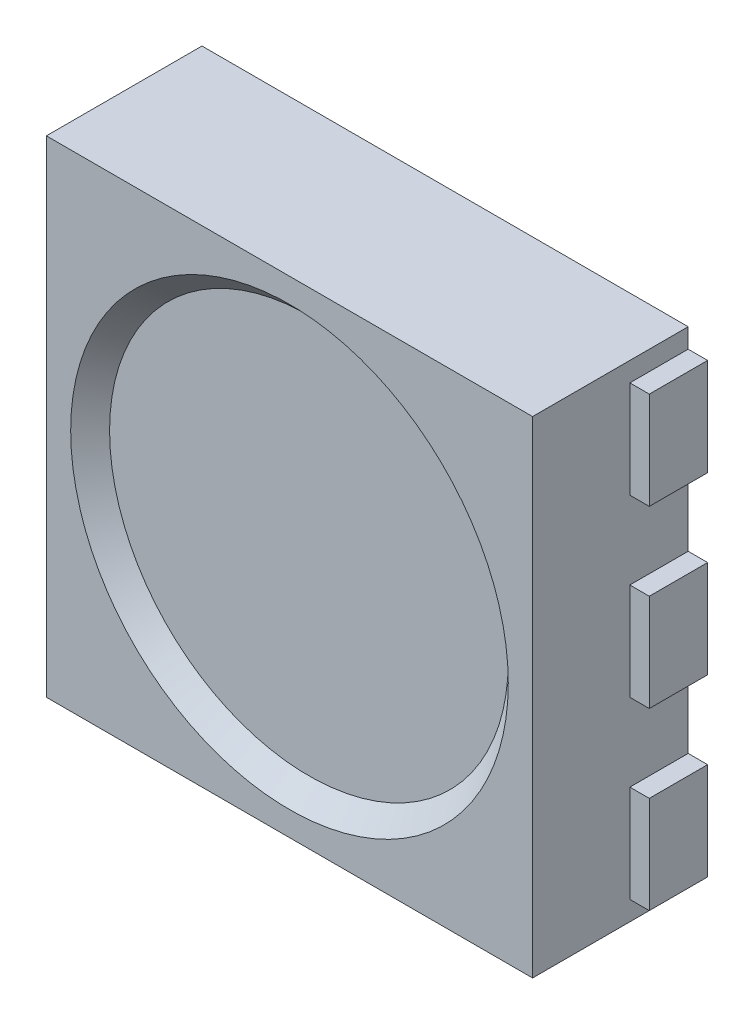
SolidWorks part; units mm, degrees
ref_plane "Front Plane" through (0, 0, 0) normal (0, 0, 1) x (1, 0, 0)
ref_plane "Top Plane" through (0, 0, 0) normal (0, 1, 0) x (1, 0, 0)
ref_plane "Right Plane" through (0, 0, 0) normal (1, 0, 0) x (0, 0, -1)
sketch "Sketch1" plane through (0, 0, 0) normal (0, 0, 1) x (1, 0, 0)
  line L1 (-2.5, 2.5) -> (2.5, 2.5)
  line L2 (-2.5, 2.5) -> (-2.5, -2.5)
  line L3 (-2.5, -2.5) -> (2.5, -2.5)
  line L4 (2.5, 2.5) -> (2.5, -2.5)
  line L5 (-2.5, 2.5) -> (2.5, -2.5) construction
  line L6 (-2.5, -2.5) -> (2.5, 2.5) construction
  point P0 (0, 0)
  dimension "D1" = 5
extrude "Boss-Extrude1" add sketch "Sketch1" along normal blind 1.6
sketch "Sketch2" plane through (0, 0, 1.6) normal (0, 0, 1) x (1, 0, 0)
  circle A0 centre (0, 0) radius 2.25
  dimension "D1" = 4.5
extrude "Cut-Extrude1" cut sketch "Sketch2" against normal blind 0.2 draft 45
sketch "Sketch3" plane through (0, 0, 0) normal (0, 0, 1) x (1, 0, 0)
  line L0 (-2.5, 2.5) -> (-2.5, -2.5) construction
  line L1 (-2.5, 2.3) -> (-2.7, 2.3)
  line L2 (-2.5, 2.3) -> (-2.5, 1.3)
  line L3 (-2.5, 1.3) -> (-2.7, 1.3)
  line L4 (-2.7, 2.3) -> (-2.7, 1.3)
  line L5 (2.5, 2.5) -> (-2.5, 2.5) construction
  line L6 (0, 0) -> (-2.5, 0) construction
  line L7 (0, 0) -> (0, 2.5) construction
  line L8 (2.7, 2.3) -> (2.7, 1.3)
  line L9 (2.5, 1.3) -> (2.7, 1.3)
  line L10 (2.5, 2.3) -> (2.5, 1.3)
  line L11 (2.5, 2.3) -> (2.7, 2.3)
  line L12 (2.5, -2.3) -> (2.7, -2.3)
  line L13 (2.5, -2.3) -> (2.5, -1.3)
  line L14 (2.5, -1.3) -> (2.7, -1.3)
  line L15 (2.7, -2.3) -> (2.7, -1.3)
  line L16 (-2.7, -2.3) -> (-2.7, -1.3)
  line L17 (-2.5, -1.3) -> (-2.7, -1.3)
  line L18 (-2.5, -2.3) -> (-2.5, -1.3)
  line L19 (-2.5, -2.3) -> (-2.7, -2.3)
  line L20 (2.5, 0.5) -> (2.5, -0.5)
  line L21 (-2.7, 0.5) -> (-2.5, 0.5)
  line L22 (-2.7, 0.5) -> (-2.7, -0.5)
  line L23 (-2.7, -0.5) -> (-2.5, -0.5)
  line L24 (-2.5, 0.5) -> (-2.5, -0.5)
  line L25 (2.7, -0.5) -> (2.5, -0.5)
  line L26 (2.7, 0.5) -> (2.7, -0.5)
  line L27 (2.7, 0.5) -> (2.5, 0.5)
  dimension "D1" = 0.2
  dimension "D2" = 1
  dimension "D3" = 0.2
extrude "Boss-Extrude2" add sketch "Sketch3" along normal blind 0.6
